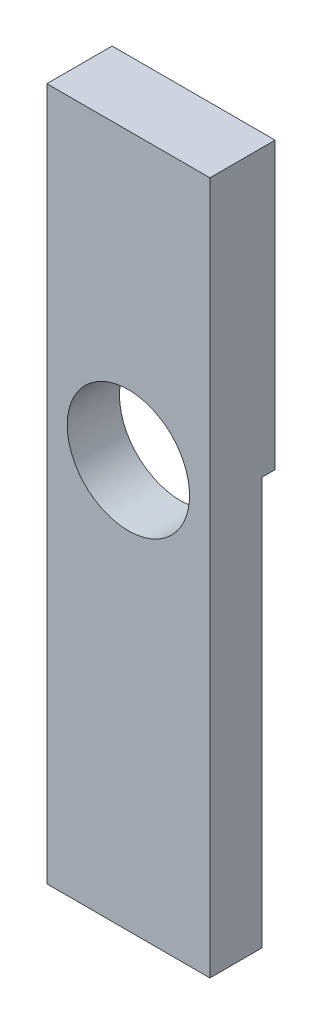
SolidWorks part; units mm, degrees
ref_plane "Front Plane" through (0, 0, 0) normal (0, 0, 1) x (1, 0, 0)
ref_plane "Top Plane" through (0, 0, 0) normal (0, 1, 0) x (1, 0, 0)
ref_plane "Right Plane" through (0, 0, 0) normal (1, 0, 0) x (0, 0, -1)
sketch "Sketch1" plane through (0, 0, 0) normal (0, 0, 1) x (1, 0, 0)
  line L0 (-6.35, 53.975) -> (-6.35, 0)
  line L1 (-6.35, 53.975) -> (6.35, 53.975)
  line L2 (-6.35, 0) -> (6.35, 0)
  line L3 (6.35, 53.975) -> (6.35, 0)
  line L4 (-6.35, 53.975) -> (6.35, 0) construction
  line L5 (-6.35, 0) -> (6.35, 53.975) construction
  point P1 (0, 26.9875)
  dimension "D1" = 12.7
  dimension "D2" = 53.975
extrude "Boss-Extrude1" add sketch "Sketch1" along normal blind 5.08
sketch "Sketch2" plane through (0, 0, 0) normal (0, 0, 1) x (1, 0, 0)
  line L0 (0, -31.75) -> (0, 31.75) construction
  line L1 (-6.35, -31.75) -> (-6.35, 31.75)
  line L2 (6.35, -31.75) -> (6.35, 31.75)
  line L3 (6.35, 53.975) -> (-6.35, 53.975) construction
  arc A0 (-6.35, -31.75) -> (6.35, -31.75) centre (0, -31.75) ccw
  arc A1 (6.35, 31.75) -> (-6.35, 31.75) centre (0, 31.75) ccw
  point P2 (0, 0)
  point P8 (0, 38.1)
  dimension "D1" = 6.35
  dimension "D2" = 15.875
extrude "Cut-Extrude1" cut sketch "Sketch2" along normal blind 1.016
sketch "Sketch3" plane through (0, 0, 1.016) normal (0, 0, -1) x (-1, 0, 0)
  circle A0 centre (0, 31.75) radius 4.7625
  arc A1 (6.35, 31.75) -> (-6.35, 31.75) centre (0, 31.75) ccw construction
  dimension "D1" = 9.525
extrude "Cut-Extrude2" cut sketch "Sketch3" against normal through all
